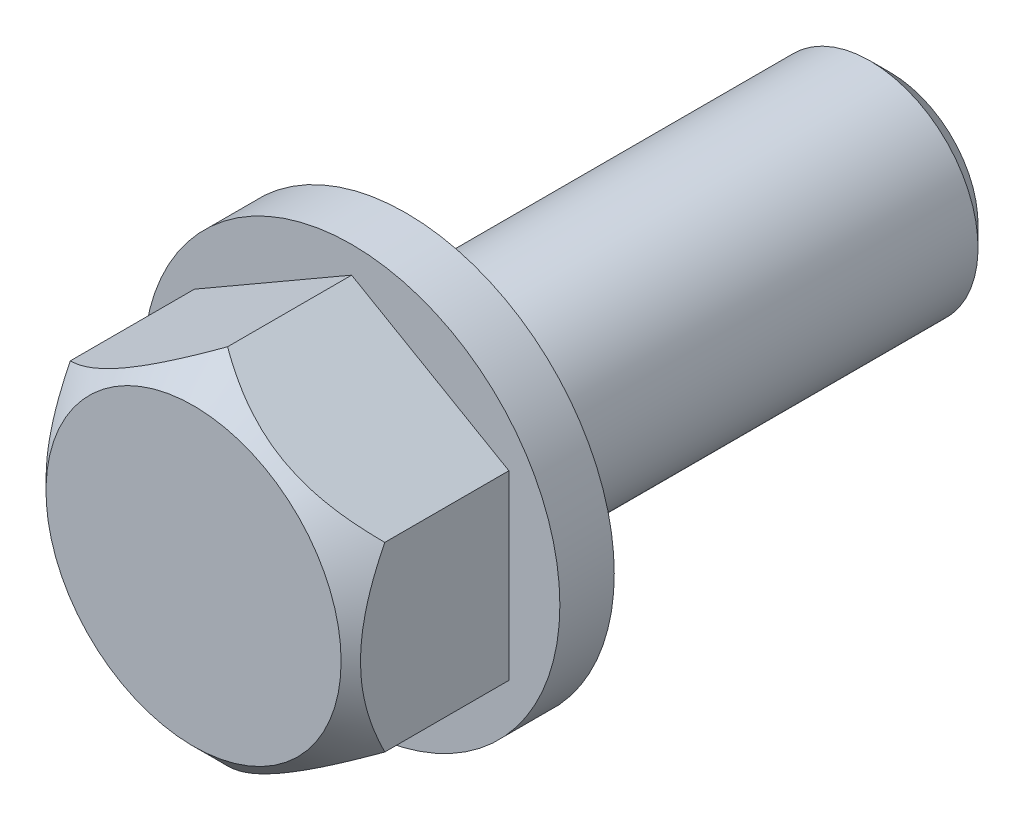
SolidWorks part; units mm, degrees
ref_plane "Front Plane" through (0, 0, 0) normal (0, 0, 1) x (1, 0, 0)
ref_plane "Top Plane" through (0, 0, 0) normal (0, 1, 0) x (1, 0, 0)
ref_plane "Right Plane" through (0, 0, 0) normal (1, 0, 0) x (0, 0, -1)
sketch "Sketch1" plane through (0, 0, 0) normal (0, 0, 1) x (1, 0, 0)
  line L1 (9.25, -5.3405) -> (9.25, 5.3405)
  line L2 (9.25, 5.3405) -> (0, 10.681)
  line L3 (0, 10.681) -> (-9.25, 5.3405)
  line L4 (-9.25, 5.3405) -> (-9.25, -5.3405)
  line L5 (-9.25, -5.3405) -> (0, -10.681)
  line L6 (0, -10.681) -> (9.25, -5.3405)
  circle A0 centre (0, 0) radius 9.25 construction
  dimension "D1" = 18.5
extrude "Boss-Extrude1" add sketch "Sketch1" against normal blind 9.3
sketch "Sketch2" plane through (0, 0, 0) normal (1, 0, 0) x (0, 0, -1)
  line L0 (9.3, 12.25) -> (12.5, 12.25)
  line L1 (9.3, 5.3405) -> (9.3, 10.681) construction
  line L2 (12.5, 12.25) -> (12.5, 6.35)
  line L3 (12.5, 6.35) -> (41, 6.35)
  line L4 (41, 6.35) -> (41, 0)
  line L5 (41, 0) -> (9.3, 0)
  line L6 (9.3, -5.3405) -> (9.3, 5.3405) construction
  line L7 (9.3, 0) -> (9.3, 12.25)
  line L8 (0, -5.3405) -> (0, 5.3405) construction
  dimension "D1" = 12.25
  dimension "D2" = 6.35
  dimension "D3" = 3.2
  dimension "D4" = 41
revolve "Revolve1" add sketch "Sketch2" angle 360 about L5
sketch "Sketch3" plane through (0, 0, 0) normal (1, 0, 0) x (0, 0, -1)
  line L0 (0, 8.681) -> (2, 10.681)
  line L1 (0, 5.3405) -> (0, 10.681) construction
  line L2 (9.3, 10.681) -> (0, 10.681) construction
  line L3 (2, 10.681) -> (0, 10.681)
  line L4 (0, 10.681) -> (0, 8.681)
  line L5 (0, 0) -> (15.7942, 0) construction
  dimension "D1" = 2
  dimension "D2" = 2
revolve "Cut-Revolve1" cut sketch "Sketch3" angle 360 about L5
chamfer "Chamfer1" distance 1.2 angle 45 1 edges at (0, 6.35, -41)
